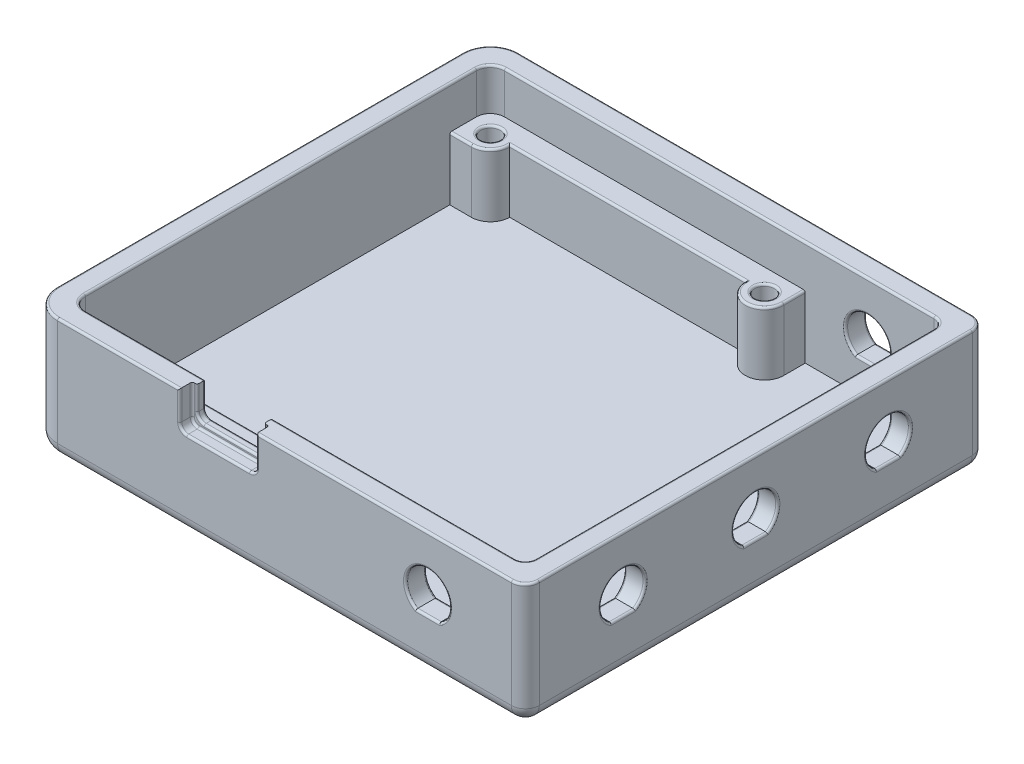
SolidWorks part; units mm, degrees
ref_plane "Front Plane" through (0, 0, 0) normal (0, 0, 1) x (1, 0, 0)
ref_plane "Top Plane" through (0, 0, 0) normal (0, 1, 0) x (1, 0, 0)
ref_plane "Right Plane" through (0, 0, 0) normal (1, 0, 0) x (0, 0, -1)
sketch "Sketch1" plane through (0, 0, 0) normal (0, 1, 0) x (1, 0, 0)
  line L1 (-32.5, 30) -> (32.5, 30)
  line L2 (-32.5, 30) -> (-32.5, -30)
  line L3 (-32.5, -30) -> (32.5, -30)
  line L4 (32.5, 30) -> (32.5, -30)
  line L5 (-32.5, 30) -> (32.5, -30) construction
  line L6 (-32.5, -30) -> (32.5, 30) construction
  line L7 (-35.5, 33) -> (35.5, 33)
  line L8 (-35.5, 33) -> (-35.5, -33)
  line L9 (-35.5, -33) -> (35.5, -33)
  line L10 (35.5, 33) -> (35.5, -33)
  line L11 (-35.5, 33) -> (35.5, -33) construction
  line L12 (-35.5, -33) -> (35.5, 33) construction
  point P0 (0, 0)
  point P6 (0, 0)
  dimension "D1" = 60
  dimension "D2" = 65
  dimension "D3" = 3
  dimension "D4" = 3
extrude "Boss-Extrude1" add sketch "Sketch1" along normal blind 15
sketch "Sketch4" plane through (0, 0, 0) normal (0, -1, 0) x (1, 0, 0)
  line L1 (-35.5, 33) -> (35.5, 33)
  line L2 (-35.5, 33) -> (-35.5, -33)
  line L3 (-35.5, -33) -> (35.5, -33)
  line L4 (35.5, 33) -> (35.5, -33)
extrude "Boss-Extrude3" add sketch "Sketch4" along normal blind 2.5
sketch "Sketch5" plane through (0, 0, 0) normal (0, 1, 0) x (1, 0, 0)
  line L0 (0, 0) -> (-9.7945, 0) construction
  line L6 (-29.42, 26.925) -> (9.831, -26.925) construction
  line L7 (-29.42, -26.925) -> (9.831, 26.925) construction
  line L10 (-29.42, 26.925) -> (9.831, 26.925) construction
  line L11 (-29.42, 26.925) -> (-29.42, -26.925) construction
  line L12 (-29.42, -26.925) -> (9.831, -26.925) construction
  line L13 (9.831, -26.925) -> (9.831, 26.925) construction
  line L14 (-26.67, -26.925) -> (7.081, -26.925)
  line L15 (12.581, -26.925) -> (12.581, -30)
  line L16 (-32.5, -30) -> (32.5, -30) construction
  line L17 (12.581, -30) -> (-32.5, -30)
  line L18 (-32.5, -30) -> (-32.5, -24.175)
  line L19 (-32.5, 30) -> (-32.5, -30) construction
  line L20 (-32.5, -24.175) -> (-29.42, -24.175)
  line L21 (-26.67, 26.925) -> (7.081, 26.925)
  line L22 (-29.42, 24.175) -> (-32.5, 24.175)
  line L23 (-32.5, 24.175) -> (-32.5, 30)
  line L24 (-32.5, 30) -> (12.581, 30)
  line L25 (32.5, 30) -> (-32.5, 30) construction
  line L26 (12.581, 30) -> (12.581, 26.925)
  circle A0 centre (-29.42, 26.925) radius 1.4
  circle A1 centre (9.831, 26.925) radius 1.4
  circle A2 centre (9.831, -26.925) radius 1.4
  circle A3 centre (-29.42, -26.925) radius 1.4
  arc A4 (-29.42, 24.175) -> (-26.67, 26.925) centre (-29.42, 26.925) ccw
  arc A5 (7.081, 26.925) -> (12.581, 26.925) centre (9.831, 26.925) ccw
  arc A6 (12.581, -26.925) -> (7.081, -26.925) centre (9.831, -26.925) ccw
  arc A7 (-26.67, -26.925) -> (-29.42, -24.175) centre (-29.42, -26.925) ccw
  dimension "D3" = 2.8
  dimension "D4" = 2.8
  dimension "D5" = 2.8
  dimension "D6" = 2.8
  dimension "D7" = 5.5
  dimension "D8" = 5.5
  dimension "D9" = 5.5
  dimension "D10" = 5.5
  dimension "D1" = 53.85
  dimension "D2" = 39.251
extrude "Boss-Extrude4" add sketch "Sketch5" along normal blind 9
fillet "Fillet1" radius 2 2 edges at (-32.5, 12, 30) (-32.5, 12, -30)
fillet "Fillet2" radius 4 2 edges at (-35.5, 6.25, -33) (-35.5, 6.25, 33)
fillet "Fillet3" radius 2 8 edges at (2, -2.5, 33) (-34.3284, -2.5, 31.8284) (-35.5, -2.5, 0) (-34.3284, -2.5, -31.8284) (35.5, 6.25, 33) (35.5, -2.5, 0) (35.5, 6.25, -33) (2, -2.5, -33)
sketch "Sketch6" plane through (0, 15, 0) normal (0, 1, 0) x (1, 0, 0)
  line L0 (-32.5, -24.175) -> (-32.5, -28) construction
  line L1 (-13.3, -27.7193) -> (-3.7, -27.7193)
  line L2 (-13.3, -27.7193) -> (-13.3, -35.9519)
  line L3 (-13.3, -35.9519) -> (-3.7, -35.9519)
  line L4 (-3.7, -27.7193) -> (-3.7, -35.9519)
  dimension "D1" = 19.2
  dimension "D2" = 9.6
extrude "Cut-Extrude1" cut sketch "Sketch6" against normal blind 4.45
fillet "Fillet4" radius 1 2 edges at (-3.7, 10.55, 31.5) (-13.3, 10.55, 31.5)
sketch "Sketch7" plane through (0, 0, 33) normal (0, 0, 1) x (1, 0, 0)
  line L0 (-13.3, 13.275) -> (-3.7, 13.275) construction
  line L1 (-14, 16.775) -> (-3, 16.775)
  line L2 (-14, 16.775) -> (-14, 9.775)
  line L3 (-14, 9.775) -> (-3, 9.775)
  line L4 (-3, 16.775) -> (-3, 9.775)
  line L5 (-14, 16.775) -> (-3, 9.775) construction
  line L6 (-14, 9.775) -> (-3, 16.775) construction
  line L7 (-13.3, 11.55) -> (-13.3, 15) construction
  line L8 (-3.7, 15) -> (-3.7, 11.55) construction
  point P0 (-8.5, 13.275)
  dimension "D1" = 11
  dimension "D2" = 7
extrude "Cut-Extrude2" cut sketch "Sketch7" against normal blind 1.8
fillet "Fillet5" radius 1 2 edges at (-3, 9.775, 32.1) (-14, 9.775, 32.1)
sketch "Sketch8" plane through (35.5, 0, 0) normal (1, 0, 0) x (0, 0, -1)
  line L0 (-31, 7.25) -> (31, 7.25) construction
  line L1 (-31, 15) -> (-31, -0.5) construction
  line L2 (31, -0.5) -> (31, 15) construction
  line L3 (-20.6714, 4.58) -> (-17.3286, 4.58)
  line L4 (-19, 10.4) -> (-19, 4.58) construction
  line L5 (-1.6714, 4.58) -> (1.6714, 4.58)
  line L6 (17.3286, 4.58) -> (20.6714, 4.58)
  arc A0 (1.6714, 4.58) -> (-1.6714, 4.58) centre (0, 7.25) ccw
  arc A1 (20.6714, 4.58) -> (17.3286, 4.58) centre (19, 7.25) ccw
  arc A2 (-17.3286, 4.58) -> (-20.6714, 4.58) centre (-19, 7.25) ccw
  dimension "D1" = 6.3
  dimension "D2" = 6.3
  dimension "D3" = 6.3
  dimension "D4" = 12
  dimension "D5" = 12
  dimension "D6" = 5.82
extrude "Cut-Extrude3" cut sketch "Sketch8" against normal up to next
sketch "Sketch9" plane through (0, 0, 33) normal (0, 0, 1) x (1, 0, 0)
  line L0 (33.5, 7.25) -> (21.5, 7.25) construction
  line L1 (33.5, -0.5) -> (33.5, 15) construction
  line L2 (19.8286, 4.58) -> (23.2414, 4.58)
  line L3 (21.5, 10.4) -> (21.535, 4.58) construction
  arc A0 (23.1714, 4.58) -> (19.8286, 4.58) centre (21.5, 7.25) ccw
  dimension "D1" = 6.3
  dimension "D2" = 5.82
  dimension "D3" = 12
extrude "Cut-Extrude4" cut sketch "Sketch9" against normal through all contours L2 A0
fillet "Fillet6" radius 0.3 24 edges at (-3, 12.8875, 31.2) (-3.2929, 10.0679, 31.2) (-8.5, 9.775, 31.2) (-13.7071, 10.0679, 31.2) (-3.7, 13.275, 31.2) (-3.9929, 10.8429, 31.2) (-8.5, 10.55, 31.2) (-13.3, 13.275, 31.2) (-3, 12.8875, 33) (-3.2929, 10.0679, 33) (-8.5, 9.775, 33) (-13.7071, 10.0679, 33) (15.25, 15, 33) (34.9142, 15, 32.4142) (35.5, 15, 0) (34.9142, 15, -32.4142) (1, 15, -33) (-34.3284, 15, -31.8284) (-35.5, 15, 0) (-34.3284, 15, 31.8284) (-14, 12.8875, 31.2) (-13.0071, 10.8429, 31.2) (-14, 12.8875, 33) (-22.75, 15, 33)
fillet "Fillet7" radius 1.5 2 edges at (32.5, 7.5, 30) (32.5, 7.5, -30)
fillet "Fillet8" radius 0.3 14 edges at (-13.3, 13.275, 30) (-13.0071, 10.8429, 30) (-8.5, 10.55, 30) (-3.9929, 10.8429, 30) (13.65, 15, 30) (32.0607, 15, 29.5607) (32.5, 15, 0) (32.0607, 15, -29.5607) (-21.9, 15, 30) (-31.9142, 15, 29.4142) (-32.5, 15, 0) (-31.9142, 15, -29.4142) (-3.7, 13.275, 30) (0.25, 15, -30)
fillet "Fillet9" radius 0.3 34 edges at (12.581, 9, 28.4625) (-27.4755, 9, 24.9805) (-30.96, 9, -24.175) (12.581, 9, -28.4625) (9.831, 9, -25.525) (-29.42, 9, -25.525) (-29.42, 9, 28.325) (9.831, 9, 28.325) (9.831, 9, 24.175) (-9.7945, 9, 26.925) (-30.96, 9, 24.175) (-27.4755, 9, -24.9805) (9.831, 9, -24.175) (-9.7945, 9, -26.925) (21.5, 4.58, -30) (21.5, 10.4, -30) (32.5, 4.58, -19) (32.5, 10.4, -19) (32.5, 4.58, 0) (32.5, 10.4, 0) (32.5, 4.58, 19) (32.5, 10.4, 19) (21.5, 4.58, 30) (21.5, 10.4, 30) (21.5, 4.58, 33) (21.5, 10.4, 33) (21.5, 4.58, -33) (21.5, 10.4, -33) (35.5, 4.58, 19) (35.5, 10.4, 19) (35.5, 4.58, 0) (35.5, 10.4, 0) (35.5, 10.4, -19) (35.5, 4.58, -19)
